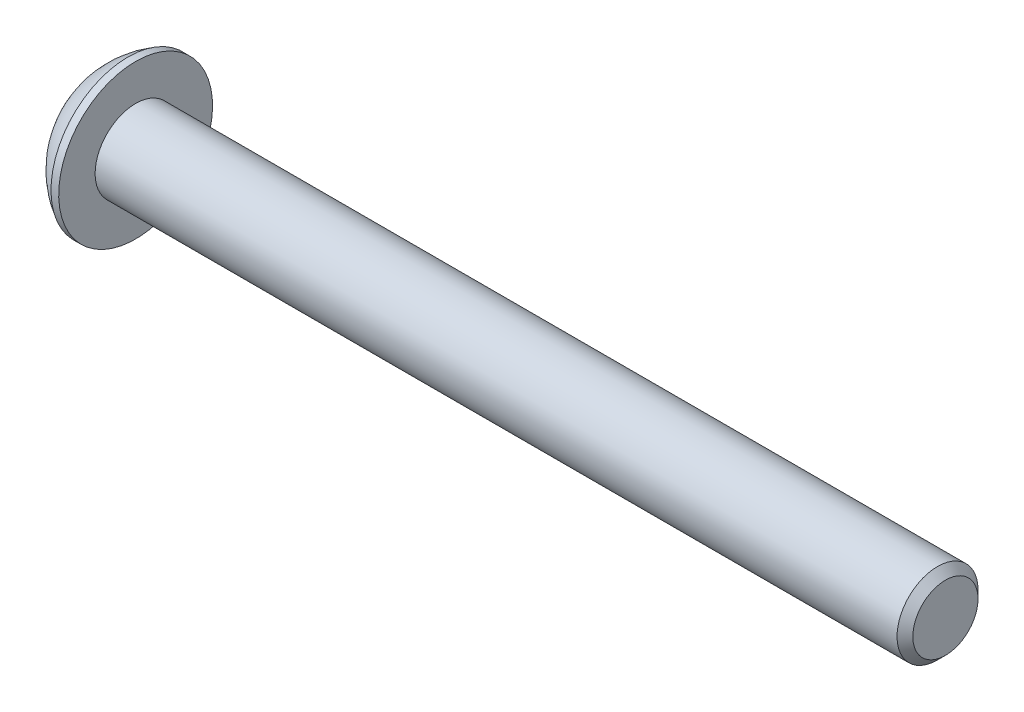
SolidWorks part; units mm, degrees
material "AISI 304"
ref_plane "Front Plane" through (0, 0, 0) normal (0, 0, 1) x (1, 0, 0)
ref_plane "Top Plane" through (0, 0, 0) normal (0, 1, 0) x (1, 0, 0)
ref_plane "Right Plane" through (0, 0, 0) normal (1, 0, 0) x (0, 0, -1)
sketch "Sketch1" plane through (0, 0, 0) normal (0, 0, 1) x (1, 0, 0)
  line L0 (42.2, 0) -> (42.2, 1.61)
  line L1 (41.81, 2) -> (2.2, 2)
  line L2 (2.2, 2) -> (2.2, 3.8)
  line L3 (2.2, 3.8) -> (1.82, 3.8)
  line L5 (42.2, 0) -> (0, 0)
  line L7 (0, 0) -> (0, 1.9)
  line L8 (42.2, 1.61) -> (41.81, 2)
  line L9 (11.1, -4.4725) -> (10.71, -4.8625) construction
  arc A0 (0, 1.9) -> (1.82, 3.8) centre (3.8853, 0) cw
  dimension "D6" = 4.325
  dimension "D1" = 3.8
  dimension "D2" = 2.2
  dimension "D3" = 2
  dimension "D4" = 0.38
  dimension "D7" = 0.39
  dimension "length" = 40
  dimension "D8" = 135
revolve "Revolve1" add sketch "Sketch1" angle 360 about L5
sketch "Sketch2" plane through (0, 0, 0) normal (-1, 0, 0) x (0, 0, 1)
  line L1 (-1.25, 0.7217) -> (-1.25, -0.7217)
  line L2 (-1.25, -0.7217) -> (0, -1.4434)
  line L3 (0, -1.4434) -> (1.25, -0.7217)
  line L4 (1.25, -0.7217) -> (1.25, 0.7217)
  line L5 (1.25, 0.7217) -> (0, 1.4434)
  line L6 (0, 1.4434) -> (-1.25, 0.7217)
  circle A0 centre (0, 0) radius 1.25 construction
  dimension "D1" = 2.5
extrude "Cut-Extrude1" cut sketch "Sketch2" against normal blind 1.5
